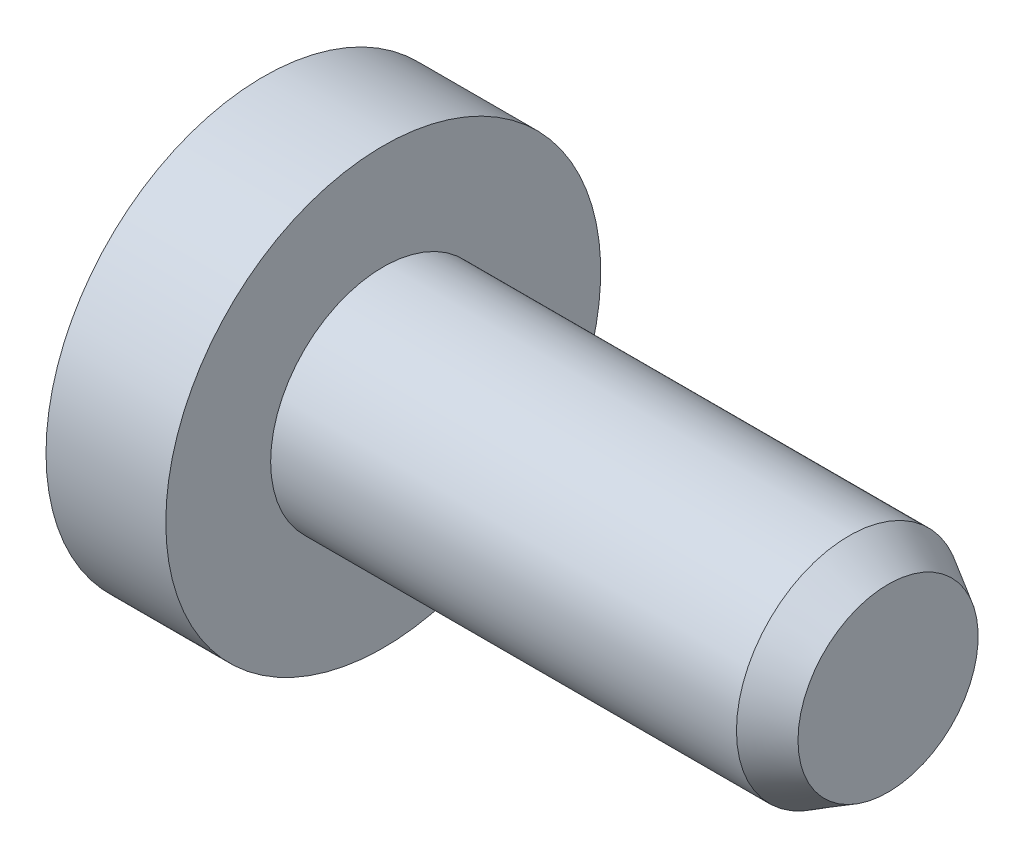
SolidWorks part; units mm, degrees
ref_plane "Front Plane" through (0, 0, 0) normal (0, 0, 1) x (1, 0, 0)
ref_plane "Top Plane" through (0, 0, 0) normal (0, 1, 0) x (1, 0, 0)
ref_plane "Right Plane" through (0, 0, 0) normal (1, 0, 0) x (0, 0, -1)
sketch "Sketch1" plane through (0, 0, 0) normal (0, 0, 1) x (1, 0, 0)
  line L0 (0, 0) -> (5.2282, 0) construction
  line L2 (0, 2.8) -> (-1.5425, 2.8)
  line L3 (-2.4, 0) -> (-2.4, -0.7496) construction
  line L4 (-2.4, 0) -> (6.5, 0)
  line L5 (0, 1.45) -> (6.5, 1.45)
  line L6 (6.5, 1.45) -> (6.5, 0)
  line L7 (0, 1.45) -> (0, 2.8)
  arc A0 (-1.5425, 2.8) -> (-2.4, 0) centre (2.6, 0) ccw
  dimension "rf" = 5
  dimension "Dk" = 5.6
  dimension "K" = 2.4
  dimension "d" = 2.9
  dimension "l" = 6.5
revolve "Revolve1" add sketch "Sketch1" angle 360 about L0
cosmetic thread "ThreadCosmetic" [suppressed] parameters "D1"=6.21, "D2"=2.18
chamfer "Chamfer1" distance 0.29 angle 60 1 edges at (6.5, 0, 1.45)
sketch "Sketch5" plane through (0, 0, 0) normal (0, 0, 1) x (1, 0, 0)
  line L0 (1.0022, 1.09) -> (0.3178, 1.09)
  line L1 (0.3178, 1.09) -> (0.11, 1.45)
  line L2 (1.0022, 1.09) -> (1.21, 1.45)
  line L3 (0.11, 1.45) -> (0.11, 1.7)
  line L4 (1.21, 1.45) -> (1.21, 1.7)
  line L5 (0.11, 1.7) -> (1.21, 1.7)
  line L6 (0.66, 1.09) -> (0.66, 0) construction
  line L7 (0, 0) -> (7.3035, 0) construction
  line L9 (5.9977, 1.45) -> (0, 1.45) construction
  line L12 (0, -1.45) -> (0, 1.45) construction
  dimension "D2" = 60
  dimension "D3" = 0.25
  dimension "advance" = 1.1
  dimension "minordia" = 2.18
  dimension "threadstart" = 0.66
revolve "ThreadSchematic" [suppressed] cut sketch "Sketch5" angle 360 about L7
pattern_linear "ThdSchPat" [suppressed] count 6 spacing 1.1 along (1, 0, 0)
sketch "Sketch2" plane through (0, 0, 0) normal (0, 0, 1) x (1, 0, 0)
  line L0 (0, 0) -> (5.7679, 0) construction
  line L1 (6.5, 0) -> (3.9885, 1.45)
  line L3 (6.5, 1.45) -> (6.5, 0) construction
  line L4 (3.9885, 1.45) -> (3.9885, 1.55)
  line L5 (3.9885, 1.55) -> (6.6, 1.55)
  line L6 (6.6, 1.55) -> (6.6, 0)
  line L7 (6.6, 0) -> (6.5, 0)
  point P9 (0, 1.45)
  dimension "D1" = 30
  dimension "D2" = 0.1
  dimension "D3" = 0.1
revolve "EndCone" [suppressed] cut sketch "Sketch2" angle 360 about L0
ref_plane "Plane4" through (-2.4, 0, 0) normal (1, 0, 0) x (0, 0, -1)
sketch "Sketch3" plane through (-2.4, 0, 0) normal (1, 0, 0) x (0, 0, -1)
  line L0 (0, 2.343) -> (0, -2.4842) construction
  line L1 (2.7661, 0) -> (-3.4558, 0) construction
  line L2 (-0.375, 1.5) -> (0.375, 1.5)
  line L3 (0.375, 1.5) -> (0.225, 0.9)
  line L4 (0, 0) -> (1.9578, 1.9578) construction
  line L5 (0.225, 0.9) -> (0.4721, 0.4721)
  line L6 (0.225, 0.9) -> (0, 0) construction
  line L7 (-0.225, 0.9) -> (-0.4721, 0.4721)
  line L8 (-0.375, 1.5) -> (-0.225, 0.9)
  line L9 (1.5, 0.375) -> (1.5, -0.375)
  line L10 (1.5, -0.375) -> (0.9, -0.225)
  line L11 (0.9, -0.225) -> (0.4721, -0.4721)
  line L12 (0.9, 0.225) -> (0.4721, 0.4721)
  line L13 (1.5, 0.375) -> (0.9, 0.225)
  line L14 (0.375, -1.5) -> (-0.375, -1.5)
  line L15 (-0.375, -1.5) -> (-0.225, -0.9)
  line L16 (-0.225, -0.9) -> (-0.4721, -0.4721)
  line L17 (0.225, -0.9) -> (0.4721, -0.4721)
  line L18 (0.375, -1.5) -> (0.225, -0.9)
  line L19 (-1.5, -0.375) -> (-1.5, 0.375)
  line L20 (-1.5, 0.375) -> (-0.9, 0.225)
  line L21 (-0.9, 0.225) -> (-0.4721, 0.4721)
  line L22 (-0.9, -0.225) -> (-0.4721, -0.4721)
  line L23 (-1.5, -0.375) -> (-0.9, -0.225)
  point P14 (0, 1.5)
  point P23 (1.5, 0)
  point P30 (0, -1.5)
  point P37 (-1.5, 0)
  dimension "D1" = 45
  dimension "m" = 3
  dimension "D3" = 0.75
  dimension "D4" = 75
  dimension "D5" = 1.8
extrude "Cut-Extrude1" cut sketch "Sketch3" along normal blind 1.4 draft 6
sketch "Sketch4" plane through (-2.4, 0, 0) normal (1, 0, 0) x (0, 0, -1)
  line L0 (0, 2.1951) -> (0, -2.1951) construction
  line L1 (2.1996, 0) -> (-2.3835, 0) construction
  line L2 (-1.3258, -1.3258) -> (1.3258, 1.3258) construction
  line L3 (1.5, 0.375) -> (-1.5, 0.375)
  line L4 (1.5, 0.375) -> (1.5, -0.375)
  line L5 (1.5, -0.375) -> (-1.5, -0.375)
  line L6 (-1.5, 0.375) -> (-1.5, -0.375)
  line L7 (0.375, 1.5) -> (-0.375, 1.5)
  line L8 (0.375, 1.5) -> (0.375, -1.5)
  line L9 (0.375, -1.5) -> (-0.375, -1.5)
  line L10 (-0.375, 1.5) -> (-0.375, -1.5)
  line L11 (1.3258, 1.3258) -> (0.6093, 0.375)
  line L12 (1.3258, 1.3258) -> (0.375, 0.6093)
  line L13 (0.375, 0.6093) -> (-0.375, 0.6093) construction
  line L14 (0, 0) -> (-1.3258, 1.3258) construction
  line L15 (-1.3258, -1.3258) -> (-0.375, -0.6093)
  line L16 (-1.3258, -1.3258) -> (-0.6093, -0.375)
  line L17 (-0.375, 0.6093) -> (-1.3258, 1.3258)
  line L18 (-1.3258, 1.3258) -> (-0.6093, 0.375)
  line L19 (-0.6093, -0.375) -> (-0.6093, 0.375) construction
  line L20 (0.6093, -0.375) -> (1.3258, -1.3258)
  line L21 (1.3258, -1.3258) -> (0.375, -0.6093)
  circle A0 centre (0, 0) radius 1.875 construction
  dimension "m" = 3
  dimension "D1" = 3.75
  dimension "D2" = 0.75
  dimension "D3" = 45
  dimension "D4" = 8
extrude "TypeZ" [suppressed] cut sketch "Sketch4" along normal blind 1.2
equation "\"D1@Chamfer1\" = \"d@Sketch1\"/10"
equation "\"D1@ThreadCosmetic\" = \"l@Sketch1\" - \"D1@Chamfer1\""
equation "\"minordia@Sketch5\" = \"D2@ThreadCosmetic\""
equation "\"D1@Plane4\" = \"K@Sketch1\""
equation "\"D5@Sketch3\" = \"m@Sketch3\" * 3 / 5"
equation "\"D3@Sketch3\" = \"m@Sketch3\" / 4"
equation "\"D2@Sketch4\" =  \"m@Sketch4\" / 4"
equation "\"D1@TypeZ\" = \"K@Sketch1\" / 2"
equation "\"m@Sketch4\" = \"m@Sketch3\""
equation "\"threadstart@Sketch5\" = \"advance@Sketch5\"*0.6"
equation "\"D1@ThdSchPat\" = int((\"l@Sketch1\"/\"advance@Sketch5\") + 0.999)"
equation "\"D3@ThdSchPat\" = \"advance@Sketch5\""
